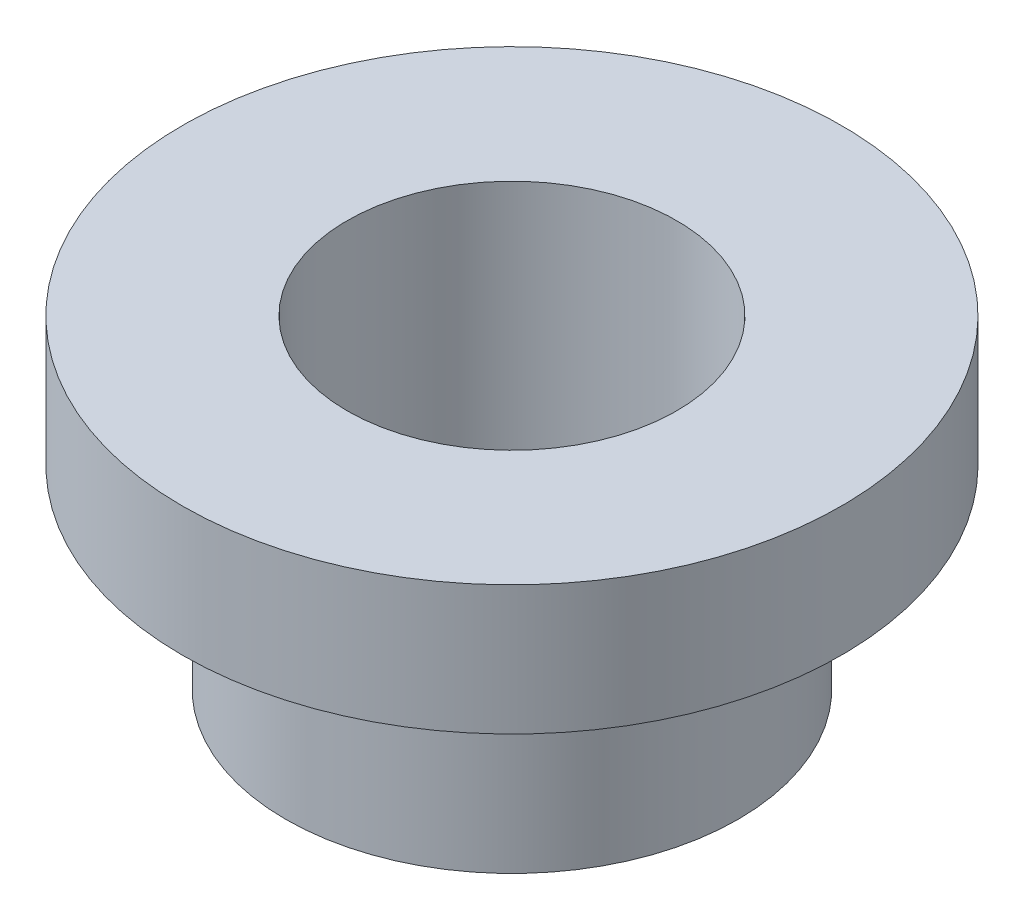
SolidWorks part; units mm, degrees
material "Nylon 101"
ref_plane "Front Plane" through (0, 0, 0) normal (0, 0, 1) x (1, 0, 0)
ref_plane "Top Plane" through (0, 0, 0) normal (0, 1, 0) x (1, 0, 0)
ref_plane "Right Plane" through (0, 0, 0) normal (1, 0, 0) x (0, 0, -1)
sketch "Sketch1" plane through (0, 0, 0) normal (1, 0, 0) x (0, 0, -1)
  line L0 (0, 8.7617) -> (0, -8.7617) construction
  line L1 (2.55, 2.5) -> (5.1, 2.5)
  line L2 (5.1, 2.5) -> (5.1, 0.5)
  line L3 (5.1, 0.5) -> (3.5, 0.5)
  line L4 (3.5, 0.5) -> (3.5, -2.5)
  line L5 (3.5, -2.5) -> (2.55, -2.5)
  line L6 (2.55, -2.5) -> (2.55, 2.5)
  line L7 (0, 0) -> (2.55, 0) construction
  dimension "D1" = 5.1
  dimension "D2" = 3.5
  dimension "D3" = 5
  dimension "D4" = 2
  dimension "D5" = 2.55
revolve "Revolve1" add sketch "Sketch1" angle 360 about L0
